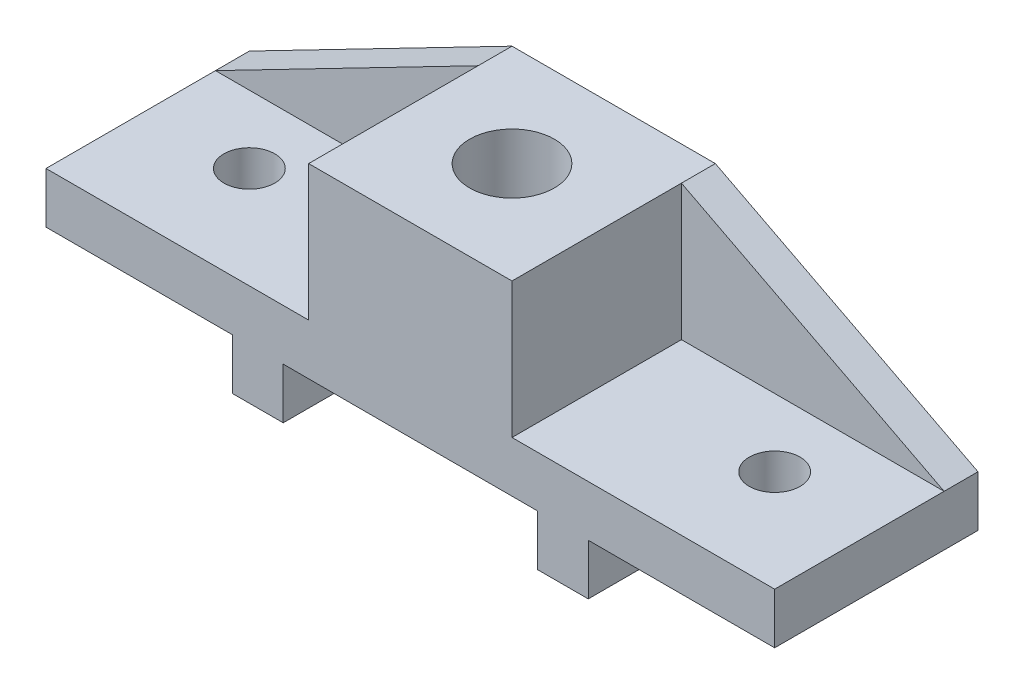
SolidWorks part; units mm, degrees
ref_plane "Front Plane" through (0, 0, 0) normal (0, 0, 1) x (1, 0, 0)
ref_plane "Top Plane" through (0, 0, 0) normal (0, 1, 0) x (1, 0, 0)
ref_plane "Right Plane" through (0, 0, 0) normal (1, 0, 0) x (0, 0, -1)
sketch "Sketch1" plane through (0, 0, 0) normal (0, 0, 1) x (1, 0, 0)
  line L0 (0, 0) -> (69.85, 0)
  line L1 (69.85, -19.05) -> (88.9, -19.05)
  line L2 (0, 0) -> (0, 19.05)
  line L3 (98.425, 69.85) -> (174.625, 69.85)
  line L4 (273.05, 0) -> (273.05, 19.05)
  line L5 (69.85, 0) -> (69.85, -19.05)
  line L6 (88.9, -19.05) -> (88.9, 0)
  line L7 (88.9, 0) -> (184.15, 0)
  line L8 (184.15, 0) -> (184.15, -19.05)
  line L9 (203.2, -19.05) -> (203.2, 0)
  line L10 (203.2, 0) -> (273.05, 0)
  line L11 (174.625, 69.85) -> (174.625, 19.05)
  line L12 (174.625, 19.05) -> (273.05, 19.05)
  line L13 (98.425, 69.85) -> (98.425, 19.05)
  line L14 (98.425, 19.05) -> (0, 19.05)
  line L15 (184.15, -19.05) -> (203.2, -19.05)
  point P0 (0, 0)
  dimension "D1" = 19.05
  dimension "D2" = 69.85
  dimension "D3" = 19.05
  dimension "D4" = 76.2
  dimension "D5" = 133.35
  dimension "D6" = 69.85
  dimension "D7" = 273.05
  dimension "D8" = 19.05
extrude "Boss-Extrude1" add sketch "Sketch1" against normal blind 76.2
sketch "Sketch2" plane through (0, 0, -76.2) normal (0, 0, -1) x (-1, 0, 0)
  line L0 (-98.425, 69.85) -> (0, 19.05)
  line L1 (-273.05, 19.05) -> (-174.625, 69.85)
  line L2 (-98.425, 69.85) -> (-98.425, 19.05)
  line L3 (-98.425, 19.05) -> (0, 19.05)
  line L4 (-174.625, 69.85) -> (-174.625, 19.05)
  line L5 (-174.625, 19.05) -> (-273.05, 19.05)
extrude "Boss-Extrude2" add sketch "Sketch2" against normal blind 12.7
sketch "Sketch3" plane through (0, 69.85, 0) normal (0, 1, 0) x (1, 0, 0)
  line L0 (174.625, 76.2) -> (98.425, 76.2) construction
  line L1 (98.425, 63.5) -> (98.425, 0) construction
  circle A0 centre (136.525, 38.1) radius 15.875
  point P14 (0, 0)
  point P15 (0, 0)
  point P17 (0, 0)
  point P18 (0, 0)
  dimension "D3" = 31.75
  dimension "D1" = 38.1
  dimension "D2" = 38.1
extrude "Cut-Extrude1" cut sketch "Sketch3" against normal through all
sketch "Sketch4" plane through (0, 19.05, 0) normal (0, 1, 0) x (1, 0, 0)
  line L0 (98.425, 0) -> (0, 0) construction
  line L1 (273.05, 0) -> (174.625, 0) construction
  line L2 (273.05, 63.5) -> (273.05, 0) construction
  line L3 (0, 63.5) -> (0, 0) construction
  circle A0 centre (234.95, 38.1) radius 9.525
  circle A1 centre (38.1, 38.1) radius 9.525
  point P10 (206.5103, 39.2074)
  dimension "D5" = 19.05
  dimension "D1" = 38.1
  dimension "D2" = 38.1
  dimension "D3" = 38.1
  dimension "D4" = 38.1
extrude "Cut-Extrude2" cut sketch "Sketch4" against normal through all
